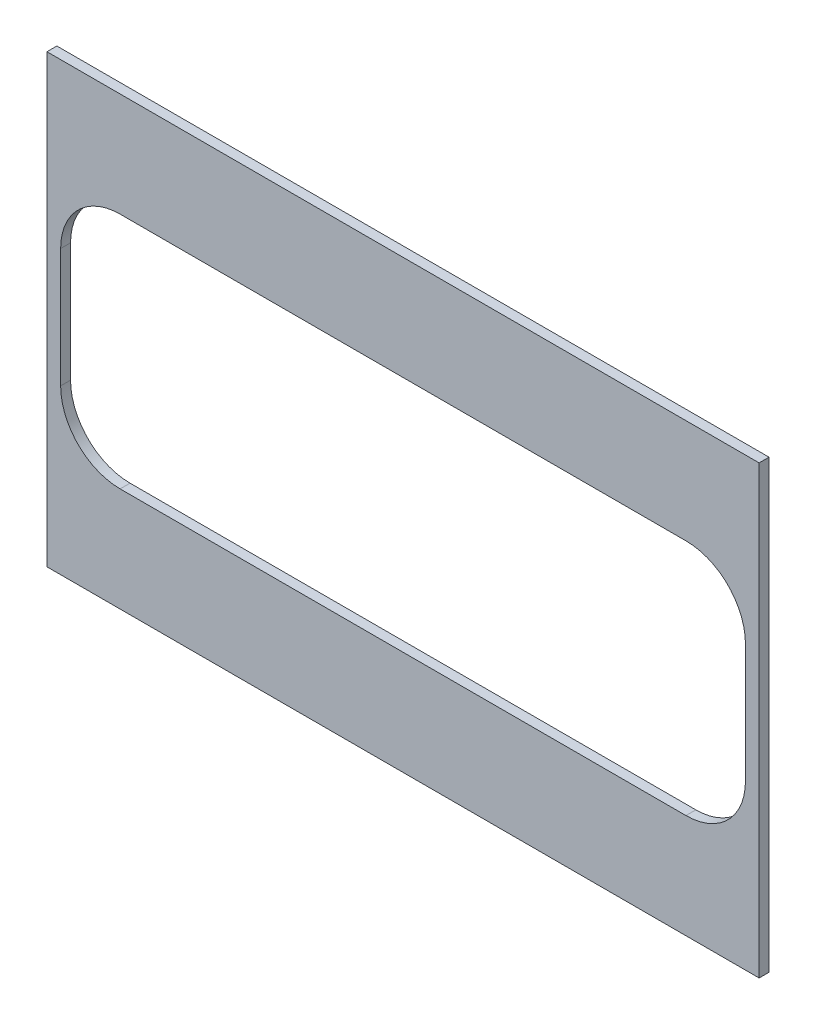
SolidWorks part; units mm, degrees
material "MDF"
ref_plane "Front Plane" through (0, 0, 0) normal (0, 0, 1) x (1, 0, 0)
ref_plane "Top Plane" through (0, 0, 0) normal (0, 1, 0) x (1, 0, 0)
ref_plane "Right Plane" through (0, 0, 0) normal (1, 0, 0) x (0, 0, -1)
sketch "Sketch1" plane through (0, 0, 0) normal (0, 0, 1) x (1, 0, 0)
  line L1 (-228.0888, 0) -> (228.0888, 0)
  line L2 (-228.0888, 0) -> (-228.0888, -285.75)
  line L3 (-228.0888, -285.75) -> (228.0888, -285.75)
  line L4 (228.0888, 0) -> (228.0888, -285.75)
  line L5 (58.5462, -285.75) -> (228.0888, -285.75) construction
  line L7 (228.0888, -3.175) -> (228.0888, -412.75) construction
  line L8 (228.0888, -412.75) -> (228.0888, -285.75) construction
  line L9 (-228.0888, -3.175) -> (-228.0888, -412.75) construction
  line L11 (-209.0388, 0) -> (-228.0888, 0) construction
extrude "Boss-Extrude1" add sketch "Sketch1" along normal blind 6.35
sketch "Sketch2" plane through (0, 0, 6.35) normal (0, 0, 1) x (1, 0, 0)
  line L0 (0, -285.75) -> (0, 0) construction
  line L1 (-228.0888, -285.75) -> (228.0888, -285.75) construction
  line L2 (228.0888, -285.75) -> (228.0888, 0) construction
  line L3 (-219.3258, -219.075) -> (219.3258, -219.075)
  line L4 (-219.3258, -219.075) -> (-219.3258, -66.675)
  line L5 (-219.3258, -66.675) -> (219.3258, -66.675)
  line L6 (219.3258, -219.075) -> (219.3258, -66.675)
  line L7 (-219.3258, -219.075) -> (219.3258, -66.675) construction
  line L8 (-219.3258, -66.675) -> (219.3258, -219.075) construction
  point P4 (0, -142.875)
  point P11 (219.3258, -240.8067)
  point P12 (0, 0)
  point P13 (0, -49.506)
  dimension "D1" = 8.763
  dimension "D2" = 152.4
extrude "Cut-Extrude1" cut sketch "Sketch2" against normal up to next
fillet "Fillet1" radius 38.1 4 edges at (219.3258, -66.675, 3.175) (219.3258, -219.075, 3.175) (-219.3258, -219.075, 3.175) (-219.3258, -66.675, 3.175)
